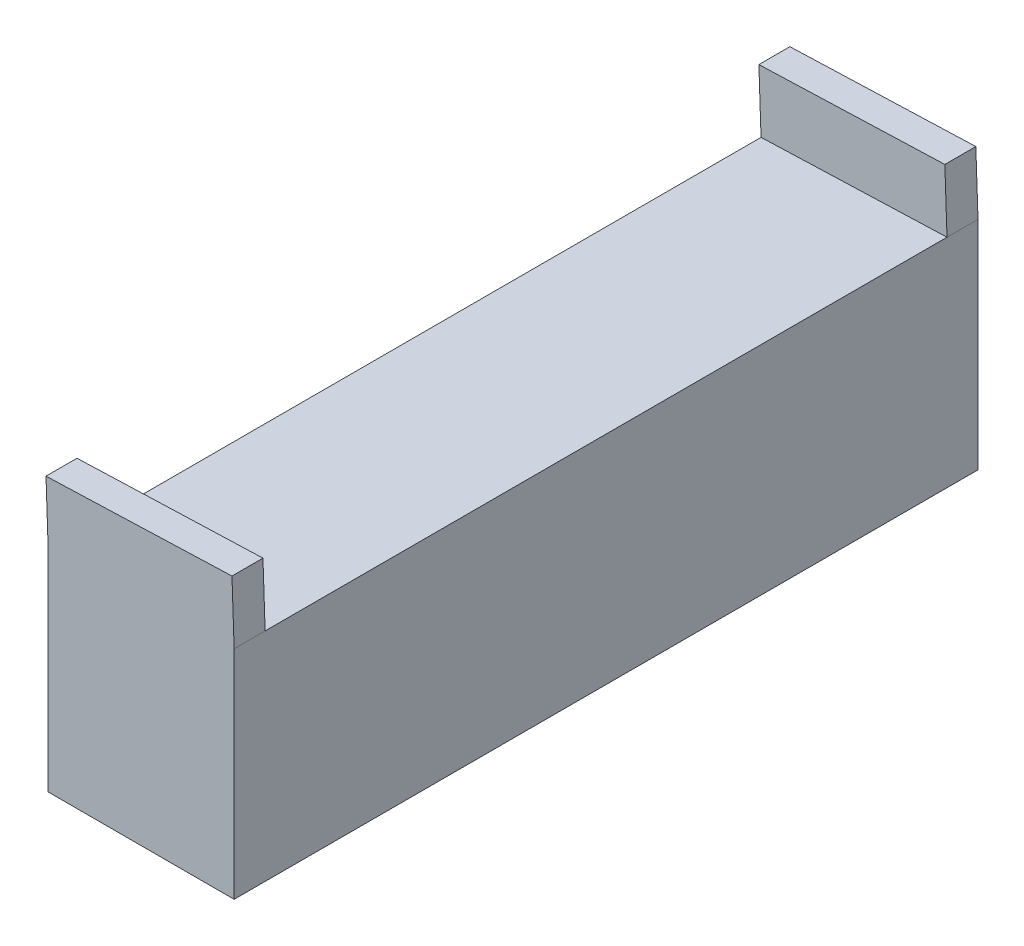
SolidWorks part; units mm, degrees
ref_plane "Спереди" through (0, 0, 0) normal (0, 0, 1) x (1, 0, 0)
ref_plane "Сверху" through (0, 0, 0) normal (0, 1, 0) x (1, 0, 0)
ref_plane "Справа" through (0, 0, 0) normal (1, 0, 0) x (0, 0, -1)
sketch "Эскиз1" plane through (708.7345, 0, -6544.7608) normal (0, 1, 0) x (1, 0, 0)
  line L1 (0, 0) -> (30, 0)
  line L2 (0, 0) -> (0, -120)
  line L3 (0, -120) -> (30, -120)
  line L4 (30, 0) -> (30, -120)
  dimension "D1" = 120
  dimension "D2" = 30
extrude "Бобышка-Вытянуть1" add sketch "Эскиз1" along normal blind 35
sketch "Эскиз3" plane through (0, 0, -6424.7608) normal (0, 0, 1) x (1, 0, 0)
  line L0 (738.7345, 35) -> (708.7345, 33.9524)
  line L1 (708.7345, 35) -> (708.7345, 0) construction
  line L2 (708.7345, 35) -> (738.7345, 35) construction
  line L3 (708.7345, 33.9524) -> (708.7345, 35)
  line L4 (708.7345, 35) -> (738.7345, 35)
  dimension "D1" = 2
extrude "Вырез-Вытянуть1" cut sketch "Эскиз3" against normal through all
sketch "Эскиз4" plane through (-0.321, 9.1916, 0) normal (-0.0349, 0.9994, 0) x (0.9994, 0.0349, 0)
  line L0 (709.4877, 6544.7608) -> (709.4877, 6424.7608) construction
  line L1 (709.4877, 6539.7608) -> (739.506, 6539.7608)
  line L2 (709.4877, 6539.7608) -> (709.4877, 6544.7608)
  line L3 (709.4877, 6544.7608) -> (739.506, 6544.7608)
  line L4 (739.506, 6539.7608) -> (739.506, 6544.7608)
  line L6 (739.506, 6424.7608) -> (709.4877, 6424.7608)
  line L7 (739.506, 6424.7608) -> (739.506, 6429.7608)
  line L8 (739.506, 6429.7608) -> (709.4877, 6429.7608)
  line L9 (709.4877, 6424.7608) -> (709.4877, 6429.7608)
  dimension "D1" = 5
  dimension "D2" = 5
extrude "Бобышка-Вытянуть2" add sketch "Эскиз4" along normal blind 10
